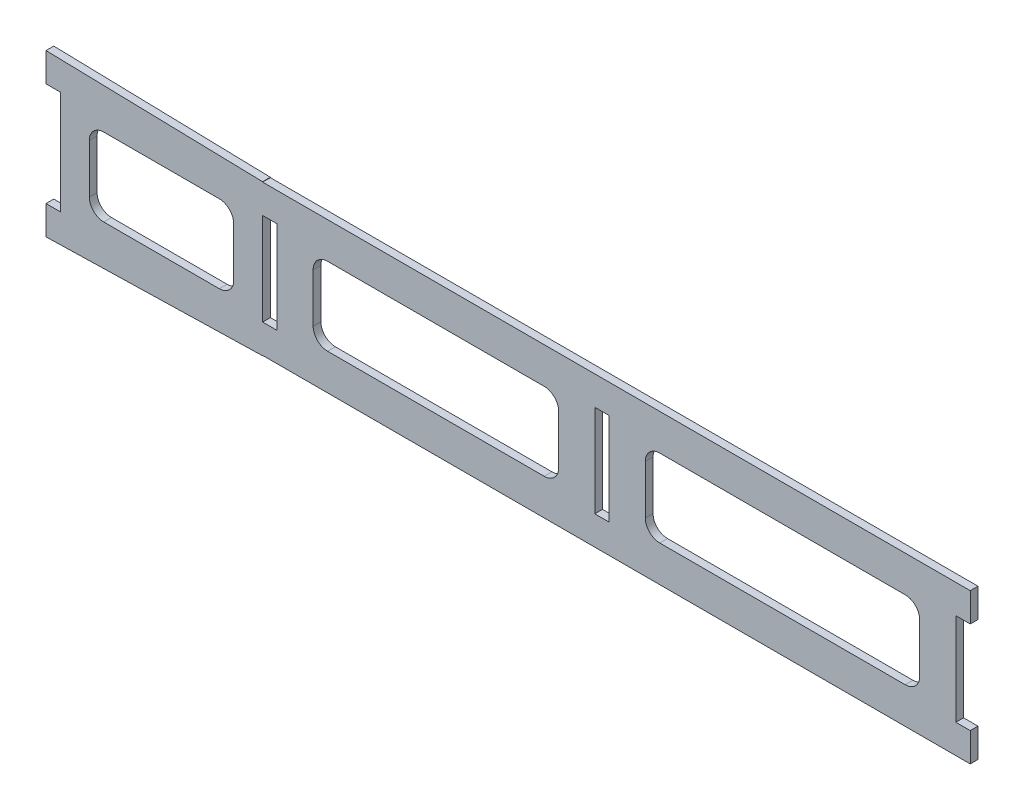
SolidWorks part; units mm, degrees
ref_plane "Front Plane" through (0, 0, 0) normal (0, 0, 1) x (1, 0, 0)
ref_plane "Top Plane" through (0, 0, 0) normal (0, 1, 0) x (1, 0, 0)
ref_plane "Right Plane" through (0, 0, 0) normal (1, 0, 0) x (0, 0, -1)
sketch "Sketch1" plane through (0, 0, 0) normal (0, 0, 1) x (1, 0, 0)
  line L0 (8565.7046, 2936.3181) -> (8660.9546, 2933.9845)
  line L1 (8565.7046, 2865.3505) -> (8660.9546, 2867.6841)
  line L2 (8660.9546, 2921.1289) -> (8660.9546, 2880.5397)
  line L3 (8572.0546, 2923.6181) -> (8572.0546, 2878.0505)
  line L4 (8667.3046, 2880.5397) -> (8660.9546, 2880.5397)
  line L5 (8667.3046, 2880.5397) -> (8667.3046, 2921.1289)
  line L6 (8683.1796, 2890.0647) -> (8683.1796, 2911.6039)
  line L7 (8667.3046, 2921.1289) -> (8660.9546, 2921.1289)
  line L8 (8565.7046, 2878.0505) -> (8565.7046, 2865.3505)
  line L9 (8565.7046, 2923.6181) -> (8565.7046, 2936.3181)
  line L10 (8648.2546, 2911.6039) -> (8648.2546, 2890.0647)
  line L11 (8641.9046, 2917.9539) -> (8591.1046, 2917.9539)
  line L12 (8591.1046, 2883.7147) -> (8641.9046, 2883.7147)
  line L13 (8584.7546, 2911.6039) -> (8584.7546, 2890.0647)
  line L14 (8565.7046, 2878.0505) -> (8572.0546, 2878.0505)
  line L15 (8565.7046, 2923.6181) -> (8572.0546, 2923.6181)
  line L16 (8972.1046, 2933.8289) -> (8660.9546, 2933.8289)
  line L17 (8943.5296, 2917.9539) -> (8835.5796, 2917.9539)
  line L18 (8784.7796, 2917.9539) -> (8689.5296, 2917.9539)
  line L19 (8660.9546, 2933.8289) -> (8660.9546, 2933.9845)
  line L20 (8972.1046, 2867.8397) -> (8660.9546, 2867.8397)
  line L21 (8943.5296, 2883.7147) -> (8835.5796, 2883.7147)
  line L22 (8784.7796, 2883.7147) -> (8689.5296, 2883.7147)
  line L23 (8660.9546, 2867.8397) -> (8660.9546, 2867.6841)
  line L24 (8807.0046, 2921.1289) -> (8807.0046, 2880.5397)
  line L25 (8791.1296, 2911.6039) -> (8791.1296, 2890.0647)
  line L26 (8813.3546, 2880.5397) -> (8807.0046, 2880.5397)
  line L27 (8813.3546, 2880.5397) -> (8813.3546, 2921.1289)
  line L28 (8829.2296, 2890.0647) -> (8829.2296, 2911.6039)
  line L29 (8965.7546, 2880.5397) -> (8965.7546, 2921.1289)
  line L30 (8949.8796, 2890.0647) -> (8949.8796, 2911.6039)
  line L31 (8972.1046, 2880.5397) -> (8972.1046, 2867.8397)
  line L32 (8813.3546, 2921.1289) -> (8807.0046, 2921.1289)
  line L33 (8972.1046, 2880.5397) -> (8965.7546, 2880.5397)
  line L34 (8972.1046, 2933.8289) -> (8972.1046, 2921.1289)
  line L35 (8972.1046, 2921.1289) -> (8965.7546, 2921.1289)
  arc A0 (8683.1796, 2890.0647) -> (8689.5296, 2883.7147) centre (8689.5296, 2890.0647) ccw
  arc A1 (8689.5296, 2917.9539) -> (8683.1796, 2911.6039) centre (8689.5296, 2911.6039) ccw
  arc A2 (8648.2546, 2911.6039) -> (8641.9046, 2917.9539) centre (8641.9046, 2911.6039) ccw
  arc A3 (8641.9046, 2883.7147) -> (8648.2546, 2890.0647) centre (8641.9046, 2890.0647) ccw
  arc A4 (8591.1046, 2917.9539) -> (8584.7546, 2911.6039) centre (8591.1046, 2911.6039) ccw
  arc A5 (8584.7546, 2890.0647) -> (8591.1046, 2883.7147) centre (8591.1046, 2890.0647) ccw
  arc A6 (8949.8796, 2911.6039) -> (8943.5296, 2917.9539) centre (8943.5296, 2911.6039) ccw
  arc A7 (8791.1296, 2911.6039) -> (8784.7796, 2917.9539) centre (8784.7796, 2911.6039) ccw
  arc A8 (8784.7796, 2883.7147) -> (8791.1296, 2890.0647) centre (8784.7796, 2890.0647) ccw
  arc A9 (8829.2296, 2890.0647) -> (8835.5796, 2883.7147) centre (8835.5796, 2890.0647) ccw
  arc A10 (8835.5796, 2917.9539) -> (8829.2296, 2911.6039) centre (8835.5796, 2911.6039) ccw
  arc A11 (8943.5296, 2883.7147) -> (8949.8796, 2890.0647) centre (8943.5296, 2890.0647) ccw
extrude "Boss-Extrude1" add sketch "Sketch1" along normal blind 3.4036
